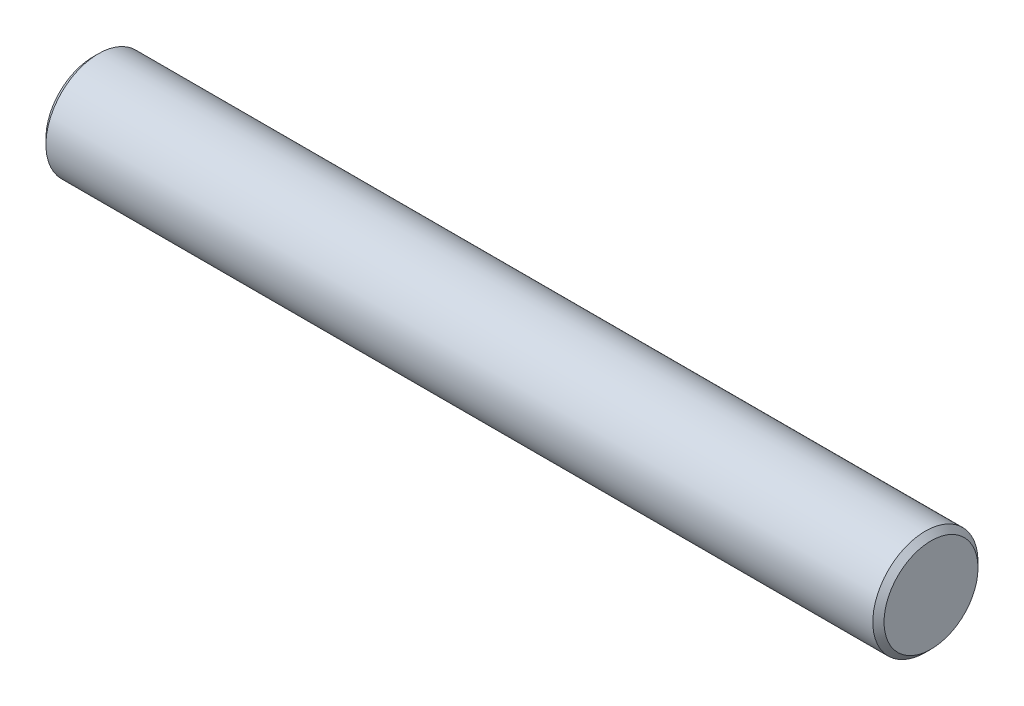
SolidWorks part; units mm, degrees
material "AISI 316 Annealed Stainless Steel Bar (SS)"
ref_plane "Front" through (0, 0, 0) normal (0, 0, 1) x (1, 0, 0)
ref_plane "Top" through (0, 0, 0) normal (0, 1, 0) x (1, 0, 0)
ref_plane "Right" through (0, 0, 0) normal (1, 0, 0) x (0, 0, -1)
sketch "Sketch1" plane through (0, 0, 0) normal (1, 0, 0) x (0, 0, -1)
  circle A0 centre (0, 0) radius 2.3749
extrude "Extrude1" add sketch "Sketch1" along normal blind 37.846
chamfer "Chamfer1" distance 0.254 angle 45 2 edges at (37.846, 0, -2.3749) (0, 0, -2.3749)
